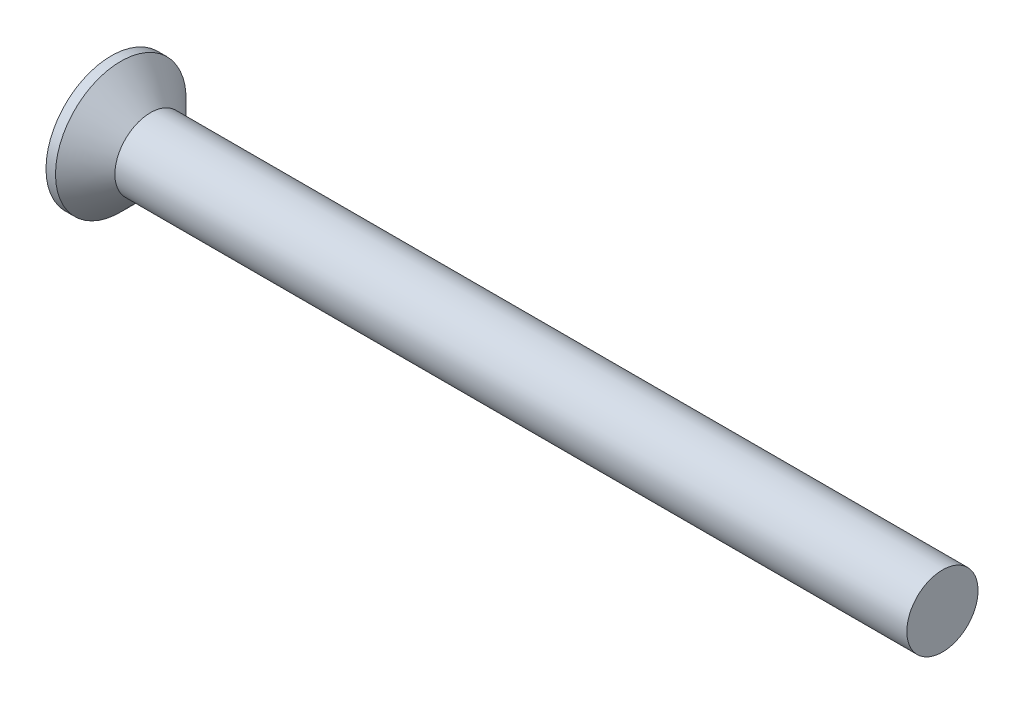
SolidWorks part; units mm, degrees
ref_plane "Plan de face" through (0, 0, 0) normal (0, 0, 1) x (1, 0, 0)
ref_plane "Plan de dessus" through (0, 0, 0) normal (0, 1, 0) x (1, 0, 0)
ref_plane "Plan de droite" through (0, 0, 0) normal (1, 0, 0) x (0, 0, -1)
sketch "Esquisse1" plane through (0, 0, 0) normal (0, 0, 1) x (1, 0, 0)
  line L0 (0, 0) -> (35, 0)
  line L1 (35, 0) -> (35, 1.5)
  line L2 (35, 1.5) -> (1.65, 1.5)
  line L4 (0, 2.75) -> (0, 0)
  line L5 (0, 2.75) -> (0.4, 2.75)
  line L6 (0.4, 2.75) -> (1.65, 1.5)
  dimension "D1" = 35
  dimension "D2" = 1.5
  dimension "D3" = 2.75
  dimension "D4" = 1.65
  dimension "D5" = 45
revolve "Révolution1" add sketch "Esquisse1" angle 360 about L0
equation "\"D3@Esquisse1\"=5.5/2"
